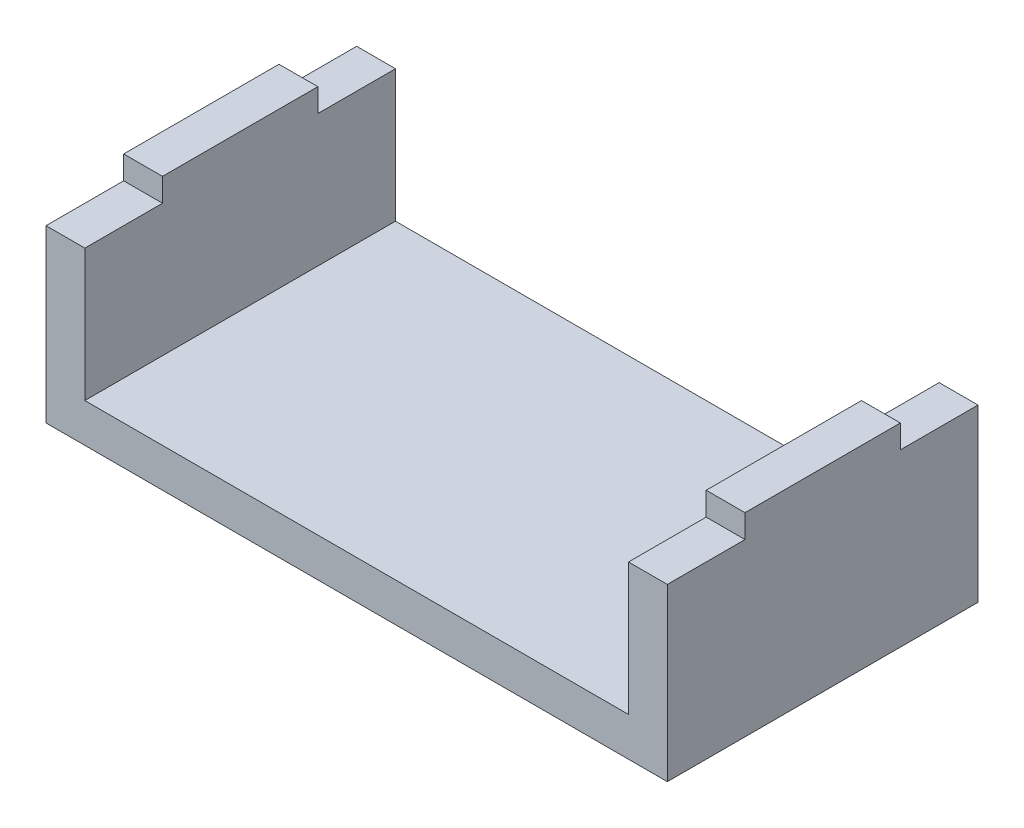
SolidWorks part; units mm, degrees
ref_plane "Front Plane" through (0, 0, 0) normal (0, 0, 1) x (1, 0, 0)
ref_plane "Top Plane" through (0, 0, 0) normal (0, 1, 0) x (1, 0, 0)
ref_plane "Right Plane" through (0, 0, 0) normal (1, 0, 0) x (0, 0, -1)
sketch "Sketch1" plane through (0, 0, 0) normal (0, 1, 0) x (1, 0, 0)
  line L1 (-40, 20) -> (40, 20)
  line L2 (-40, 20) -> (-40, -20)
  line L3 (-40, -20) -> (40, -20)
  line L4 (40, 20) -> (40, -20)
  point P4 (0, 0)
  point P5 (0, 0)
  point P6 (0, 0)
  point P7 (0, 0)
extrude "Boss-Extrude1" add sketch "Sketch1" along normal blind 5
sketch "Sketch2" plane through (0, 5, 0) normal (0, 1, 0) x (1, 0, 0)
  line L0 (-40, -20) -> (40, -20) construction
  line L1 (-40, 20) -> (-35, 20)
  line L2 (-40, 20) -> (-40, -20)
  line L3 (-40, -20) -> (-35, -20)
  line L4 (-35, 20) -> (-35, -20)
extrude "Boss-Extrude2" add sketch "Sketch2" along normal blind 20
sketch "Sketch3" plane through (0, 5, 0) normal (0, 1, 0) x (1, 0, 0)
  line L1 (40, 20) -> (35, 20)
  line L2 (40, 20) -> (40, -20)
  line L3 (40, -20) -> (35, -20)
  line L4 (35, 20) -> (35, -20)
extrude "Boss-Extrude3" add sketch "Sketch3" along normal blind 20
sketch "Sketch4" plane through (0, 25, 0) normal (0, 1, 0) x (1, 0, 0)
  line L1 (-40, 20) -> (-35, 20)
  line L2 (-40, 20) -> (-40, 10)
  line L3 (-40, 10) -> (-35, 10)
  line L4 (-35, 20) -> (-35, 10)
  line L5 (-40, -10) -> (-35, -10)
  line L6 (-40, -10) -> (-40, -20)
  line L7 (-40, -20) -> (-35, -20)
  line L8 (-35, -10) -> (-35, -20)
extrude "Cut-Extrude1" cut sketch "Sketch4" against normal blind 3
sketch "Sketch5" plane through (0, 25, 0) normal (0, 1, 0) x (1, 0, 0)
  line L1 (40, -20) -> (35, -20)
  line L2 (40, -20) -> (40, -10)
  line L3 (40, -10) -> (35, -10)
  line L4 (35, -20) -> (35, -10)
  line L5 (40, 10) -> (35, 10)
  line L6 (40, 10) -> (40, 20)
  line L7 (40, 20) -> (35, 20)
  line L8 (35, 10) -> (35, 20)
extrude "Cut-Extrude2" cut sketch "Sketch5" against normal blind 3
hole_wizard "M3 Clearance Hole1" positions "Sketch6" profile "Sketch7" hole size "M3" standard "ANSI Metric"
sketch "Sketch6" plane through (0, 0, 0) normal (0, -1, 0) x (-1, 0, 0)
  point P0 (37.5, -17.5)
  point P2 (37.5, 17.5)
  point P4 (-37.5, 17.5)
  point P6 (-37.5, -17.5)
  point P9 (0, 0)
  point P10 (0, 0)
  point P11 (0, 0)
  point P12 (0, 0)
sketch "Sketch7" plane through (-37.5, 0, 17.5) normal (1, 0, 0) x (0, 0, -1)
  line L0 (0, 0) -> (0, 6.0215)
  line L1 (0, 6.0215) -> (1.7, 5)
  line L2 (1.7, 5) -> (1.7, 0)
  line L5 (1.7, 0) -> (0, 0)
  line L10 (0, 6.0215) -> (-1.7, 5) construction
  line L11 (0, -6.35) -> (0, 107.95) construction
  dimension "Hole Dia." = 3.4
  dimension "Hole Depth" = 5
  dimension "Drill Angle" = 118
